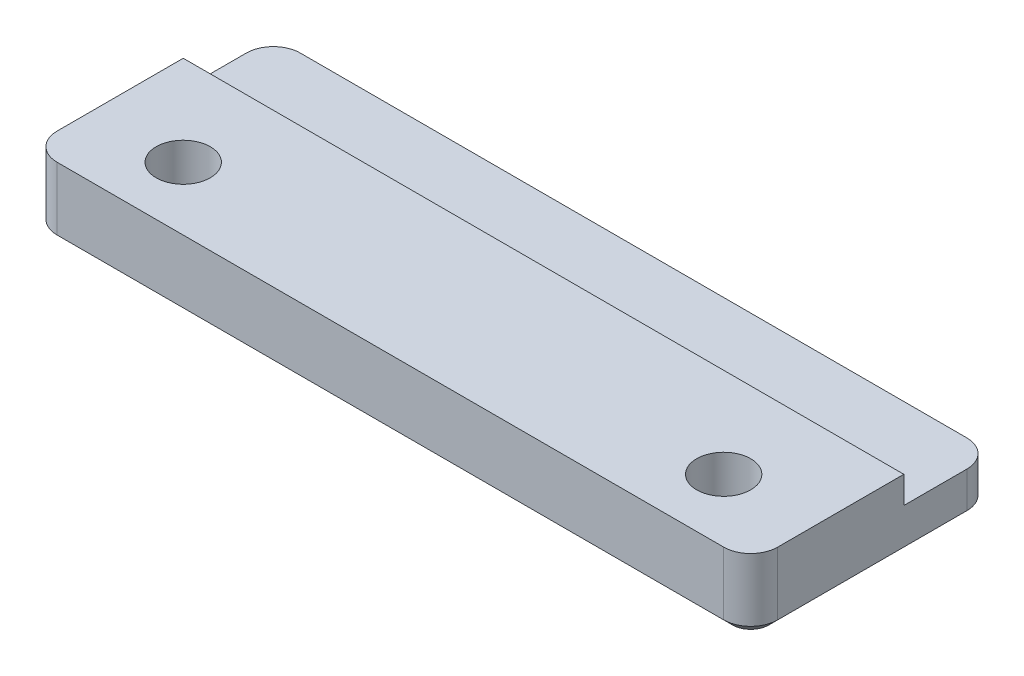
SolidWorks part; units mm, degrees
ref_plane "Front Plane" through (0, 0, 0) normal (0, 0, 1) x (1, 0, 0)
ref_plane "Top Plane" through (0, 0, 0) normal (0, 1, 0) x (1, 0, 0)
ref_plane "Right Plane" through (0, 0, 0) normal (1, 0, 0) x (0, 0, -1)
sketch "Sketch1" plane through (0, 0, 0) normal (0, 1, 0) x (1, 0, 0)
  line L1 (-40, 20) -> (40, 20)
  line L2 (-40, 20) -> (-40, -7)
  line L4 (40, 20) -> (40, -7)
  line L5 (-40, 20) -> (40, -20) construction
  line L6 (-40, -20) -> (40, 20) construction
  line L7 (30, -7) -> (40, -7)
  line L9 (30, -7) -> (-40, -7)
  circle A0 centre (30, 0) radius 3
  circle A1 centre (-30, 0) radius 3
  point P0 (0, 0)
extrude "Boss-Extrude1" add sketch "Sketch1" along normal blind 8
sketch "Sketch2" plane through (40, 0, 0) normal (1, 0, 0) x (0, 0, -1)
  line L1 (20, 8) -> (10, 8)
  line L2 (20, 8) -> (20, 5)
  line L3 (20, 5) -> (10, 5)
  line L4 (10, 8) -> (10, 5)
extrude "Cut-Extrude1" cut sketch "Sketch2" against normal through all
fillet "Fillet1" radius 3 4 edges at (-40, 2.5, -20) (-40, 4, 7) (40, 4, 7) (40, 2.5, -20)
chamfer "Chamfer1" distance 1 angle 45 10 edges at (-30, 0, 3) (30, 0, 3) (-39.1213, 0, 6.1213) (0, 0, 7) (39.1213, 0, 6.1213) (40, 0, -6.5) (39.1213, 0, -19.1213) (0, 0, -20) (-39.1213, 0, -19.1213) (-40, 0, -6.5)
